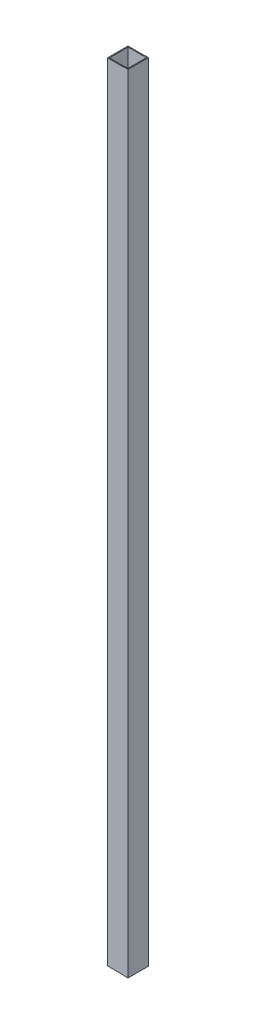
SolidWorks part; units mm, degrees
ref_plane "Front Plane" through (0, 0, 0) normal (0, 0, 1) x (1, 0, 0)
ref_plane "Top Plane" through (0, 0, 0) normal (0, 1, 0) x (1, 0, 0)
ref_plane "Right Plane" through (0, 0, 0) normal (1, 0, 0) x (0, 0, -1)
sketch "Sketch1" plane through (0, 0, 0) normal (0, 1, 0) x (1, 0, 0)
  line L0 (0, 0) -> (0, 50)
  line L1 (0, 50) -> (50, 50)
  line L2 (50, 50) -> (50, 0)
  line L3 (50, 0) -> (0, 0)
  line L4 (2.2, 47.8) -> (47.8, 47.8)
  line L5 (47.8, 47.8) -> (47.8, 2.2)
  line L6 (47.8, 2.2) -> (2.2, 2.2)
  line L7 (2.2, 2.2) -> (2.2, 47.8)
  dimension "D1" = 50
  dimension "D2" = 50
  dimension "D3" = 2.2
extrude "Boss-Extrude1" add sketch "Sketch1" along normal blind 1923
sketch "Sketch2" plane through (0, 0, 0) normal (0, 0, 1) x (1, 0, 0)
  line L0 (0, 0) -> (0, 0.5)
  line L1 (0, 1923) -> (0, 0) construction
  line L2 (0, 0.5) -> (40, 0.5)
  line L3 (40, 0.5) -> (40, 0)
  line L5 (40, 0) -> (0, 0)
  line L6 (0, 1923) -> (40, 1923)
  line L7 (0, 1923) -> (50, 1923) construction
  line L8 (40, 1923) -> (40, 1922.5)
  line L9 (40, 1922.5) -> (0, 1922.5)
  line L10 (0, 1922.5) -> (0, 1923)
  dimension "D1" = 0.5
  dimension "D2" = 40
  dimension "D3" = 0.5
  dimension "D4" = 40
extrude "Cut-Extrude2" cut sketch "Sketch2" against normal blind 50
equation "\"SquareTube_length\"=1923.0"
equation "\"D1@Boss-Extrude1\"=\"SquareTube_length\""
equation "\"SquareTube_inBack1_cutDepth50_R\"=50"
equation "\"D1@Sketch2\" = \"SquareTube_inBack7_cutDepth50_R\""
equation "\"SquareTube_inBack1_cutDepth50_L\"=50"
equation "\"D3@Sketch2\" = \"SquareTube_inBack7_cutDepth50_L\""
equation "\"CarBeamWidth\"=700.0"
equation "\"MetalSheet_3mm_length\"=5030.0"
equation "\"MetalSheet_3mm_width\"=1923.0"
equation "\"MetalSheet_3mm_FloorCut_L_length\"=1764.0"
equation "\"MetalSheet_3mm_FloorCut_L_disdance\"=1665.0"
equation "\"MetalSheet_3mm_FloorCut_R_length\"=1764.0"
equation "\"MetalSheet_3mm_FloorCut_R_disdance\"=1665.0"
equation "\"indoorHeight\"=1940.0"
equation "\"x\"=66.0"
equation "\"da\"=62.0"
equation "\"SquareTube_wheel_length\"= 750"
equation "\"channelSteel_length\"=5030.0"
equation "\"SquareTube_inFront1_cutDepth50_R\"=0.5"
equation "\"SquareTube_inFront1_cutDepth50_L\"=0.5"
equation "\"SquareTube_inFront2_cutDepth50_R\"=0.5"
equation "\"SquareTube_inFront2_cutDepth50_L\"=0.5"
equation "\"SquareTube_inFront3_cutDepth50_R\"=0.5"
equation "\"SquareTube_inFront3_cutDepth50_L\"=0.5"
equation "\"SquareTube_inFront4_cutDepth50_R\"=0.5"
equation "\"SquareTube_inFront4_cutDepth50_L\"=0.5"
equation "\"SquareTube_inFront5_cutDepth50_R\"=50"
equation "\"SquareTube_inFront5_cutDepth50_L\"=50"
equation "\"SquareTube_inFront6_cutDepth50_R\"=50"
equation "\"SquareTube_inFront6_cutDepth50_L\"=50"
equation "\"SquareTube_inFront7_cutDepth50_R\"=50"
equation "\"SquareTube_inFront7_cutDepth50_L\"=50"
equation "\"SquareTube_inFront8_cutDepth50_R\"=50"
equation "\"SquareTube_inFront8_cutDepth50_L\"=50"
equation "\"SquareTube_inFront9_cutDepth50_R\"=50"
equation "\"SquareTube_inFront9_cutDepth50_L\"=50"
equation "\"SquareTube_inFront10_cutDepth50_R\"=50"
equation "\"SquareTube_inFront10_cutDepth50_L\"=50"
equation "\"SquareTube_inBack2_cutDepth50_R\"=50"
equation "\"SquareTube_inBack2_cutDepth50_L\"=50"
equation "\"SquareTube_inBack3_cutDepth50_R\"=50"
equation "\"SquareTube_inBack3_cutDepth50_L\"=50"
equation "\"SquareTube_inBack4_cutDepth50_R\"=50"
equation "\"SquareTube_inBack4_cutDepth50_L\"=50"
equation "\"SquareTube_inBack5_cutDepth50_R\"=50"
equation "\"SquareTube_inBack5_cutDepth50_L\"=50"
equation "\"SquareTube_inBack6_cutDepth50_R\"=0.5"
equation "\"SquareTube_inBack6_cutDepth50_L\"=0.5"
equation "\"SquareTube_inFront11_cutDepth50_R\"=50"
equation "\"SquareTube_inFront11_cutDepth50_L\"=50"
equation "\"SquareTube_inFront12_cutDepth50_R\"=50"
equation "\"SquareTube_inFront12_cutDepth50_L\"=50"
equation "\"SquareTube_inFront13_cutDepth50_R\"=50"
equation "\"SquareTube_inFront13_cutDepth50_L\"=50"
equation "\"SquareTube_inFront14_cutDepth50_R\"=50"
equation "\"SquareTube_inFront14_cutDepth50_L\"=50"
equation "\"SquareTube_inBack7_cutDepth50_R\"=0.5"
equation "\"SquareTube_inBack7_cutDepth50_L\"=0.5"
equation "\"SquareTube_inBack8_cutDepth50_R\"=0.5"
equation "\"SquareTube_inBack8_cutDepth50_L\"=0.5"
